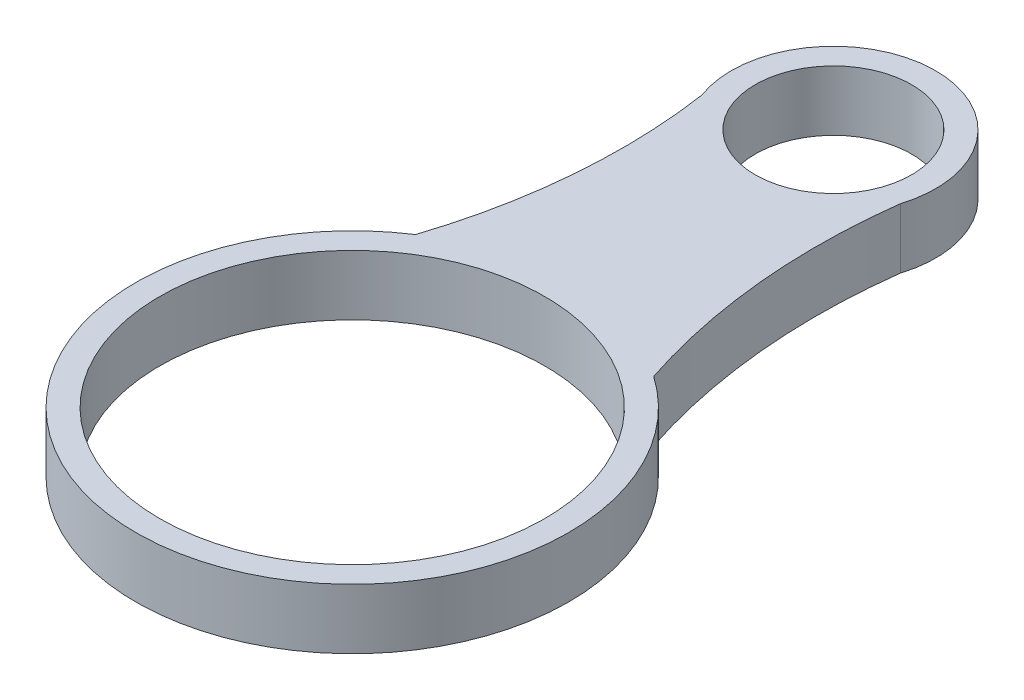
SolidWorks part; units mm, degrees
ref_plane "Front Plane" through (0, 0, 0) normal (0, 0, 1) x (1, 0, 0)
ref_plane "Top Plane" through (0, 0, 0) normal (0, 1, 0) x (1, 0, 0)
ref_plane "Right Plane" through (0, 0, 0) normal (1, 0, 0) x (0, 0, -1)
sketch "Sketch1" plane through (0, 0, 0) normal (0, 1, 0) x (1, 0, 0)
  line L0 (0, 0) -> (0, -400)
  line L1 (85, 0) -> (180, -400)
  line L2 (-85, 0) -> (-180, -400)
  line L3 (288.2714, -299.9332) -> (-553.2714, -100.0668) construction
  line L4 (-326.8938, -309.106) -> (591.8938, -90.894) construction
  circle A0 centre (0, 0) radius 85
  circle A1 centre (0, -400) radius 180
  circle A2 centre (-553.2714, -100.0668) radius 478.8439
  circle A3 centre (591.8938, -90.894) radius 514.9787
  point P12 (-132.5, -200)
  point P15 (132.5, -200)
extrude "Boss-Extrude1" add sketch "Sketch1" along normal blind 50
sketch "Sketch4" plane through (0, 50, 0) normal (0, 1, 0) x (1, 0, 0)
  line L0 (-180, -400) -> (180, -400) construction
  arc A0 (-98.2325, -249.1677) -> (102.8573, -252.2828) centre (0, -400) ccw construction
  circle A1 centre (0, -400) radius 160
sketch "Sketch5" plane through (0, 50, 0) normal (0, 1, 0) x (1, 0, 0)
  line L0 (-85, 0) -> (85, 0) construction
  arc A0 (81.0834, -25.5045) -> (-79.6152, -29.7729) centre (0, 0) ccw construction
  circle A1 centre (0, 0) radius 65
extrude "Cut-Extrude3" cut sketch "Sketch5" against normal blind 50
extrude "Cut-Extrude4" cut sketch "Sketch4" against normal blind 50
